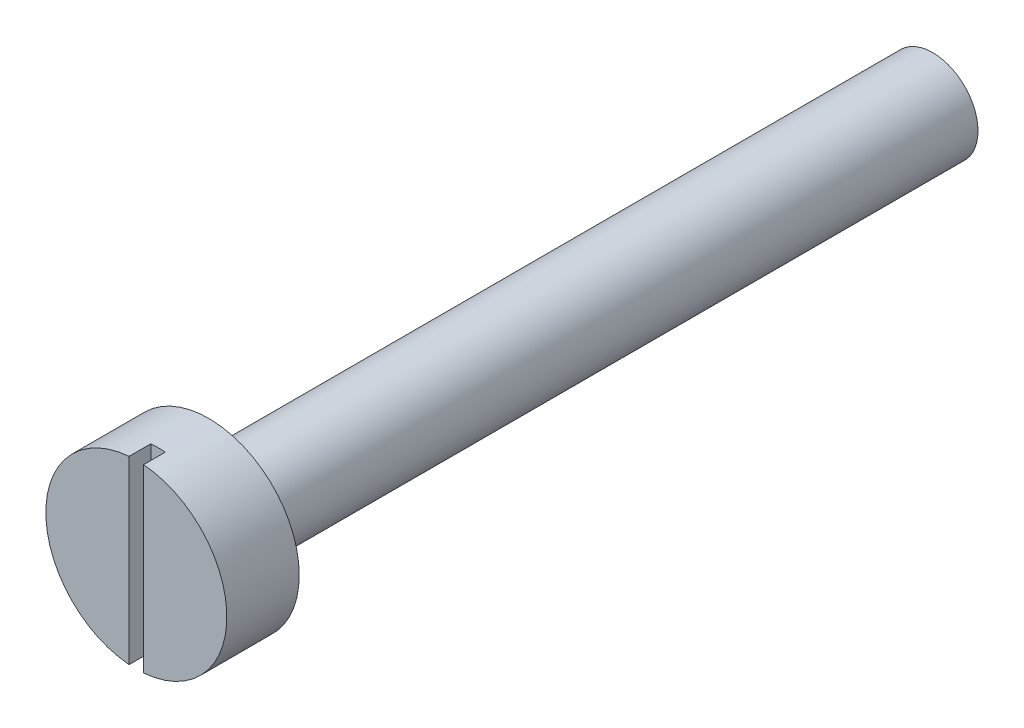
SolidWorks part; units mm, degrees
ref_plane "Спереди" through (0, 0, 0) normal (0, 0, 1) x (1, 0, 0)
ref_plane "Сверху" through (0, 0, 0) normal (0, 1, 0) x (1, 0, 0)
ref_plane "Справа" through (0, 0, 0) normal (1, 0, 0) x (0, 0, -1)
sketch "Эскиз1" plane through (0, 0, 0) normal (0, 0, 1) x (1, 0, 0)
  circle A0 centre (0, 0) radius 2.5
  dimension "D1" = 5
extrude "Вытянуть1" add sketch "Эскиз1" along normal blind 35 and the other way blind 5
sketch "Эскиз2" plane through (0, 0, 35) normal (0, 0, 1) x (1, 0, 0)
  circle A0 centre (0, 0) radius 5
  dimension "D1" = 10
extrude "Вытянуть2" add sketch "Эскиз2" along normal blind 4
sketch "Эскиз3" plane through (0, 0, 39) normal (0, 0, 1) x (1, 0, 0)
  line L0 (0, 1.8714) -> (0, -1.7382) construction
  line L1 (-0.4, -5.4661) -> (0.4, -5.4661)
  line L2 (-0.4, -5.4661) -> (-0.4, 5.5549)
  line L3 (-0.4, 5.5549) -> (0.4, 5.5549)
  line L4 (0.4, -5.4661) -> (0.4, 5.5549)
  dimension "D1" = 0.8
extrude "Вырез-Вытянуть1" cut sketch "Эскиз3" against normal blind 1.2
